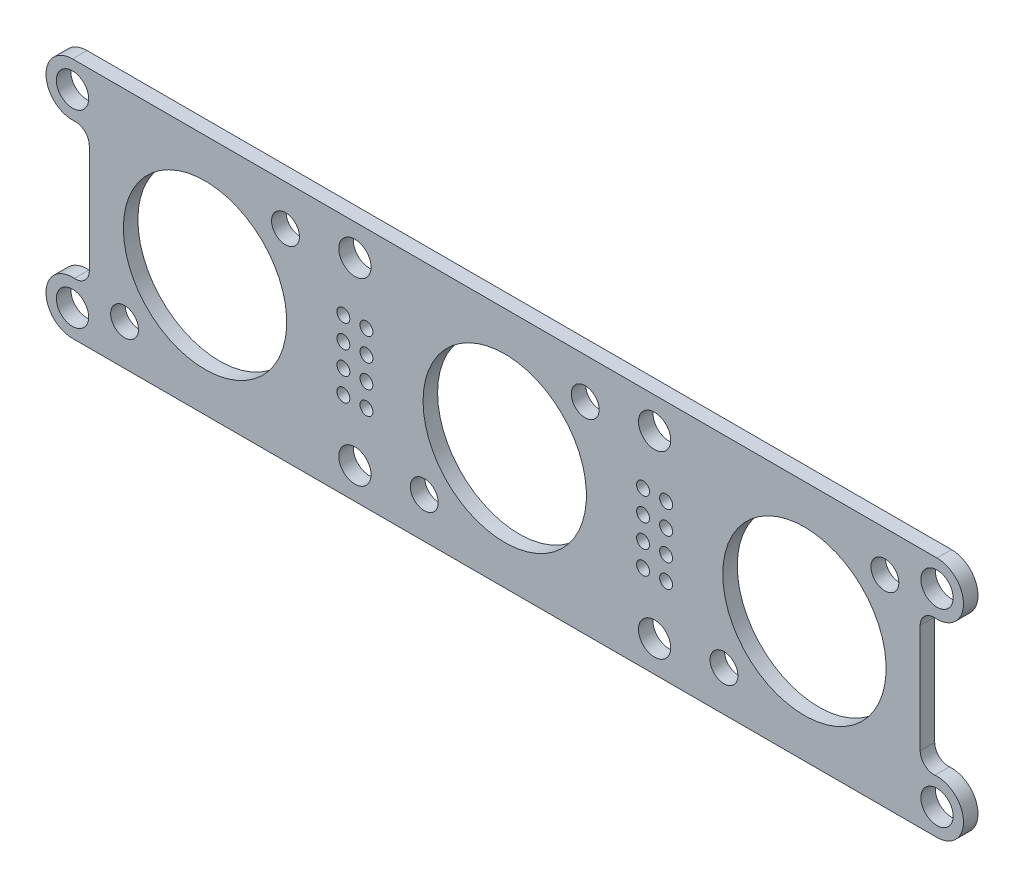
SolidWorks part; units mm, degrees
ref_plane "Front Plane" through (0, 0, 0) normal (0, 0, 1) x (1, 0, 0)
ref_plane "Top Plane" through (0, 0, 0) normal (0, 1, 0) x (1, 0, 0)
ref_plane "Right Plane" through (0, 0, 0) normal (1, 0, 0) x (0, 0, -1)
sketch "Sketch1" plane through (0, 0, -38.7925) normal (0, 0, -1) x (-1, 0, 0)
  line L72 (23.8125, 6.6675) -> (-23.8125, 6.6675)
  line L74 (-23.8125, -6.6675) -> (23.8125, -6.6675)
  line L75 (22.887, -2.9905) -> (22.887, 2.9905)
  line L76 (23.8125, 6.6675) -> (-23.8125, 6.6675)
  line L78 (-23.8125, -6.6675) -> (23.8125, -6.6675)
  line L152 (-22.887, 2.9905) -> (-22.887, -2.9905)
  line L153 (-22.887, 2.9905) -> (-22.887, -2.9905)
  line L164 (22.887, -2.9905) -> (22.887, 2.9905)
  circle A74 centre (16.51, 0) radius 4.5 construction
  circle A75 centre (0, 0) radius 4.5 construction
  circle A76 centre (-16.51, 0) radius 4.5 construction
  arc A78 (23.7051, 3.7505) -> (23.8125, 6.6675) centre (23.8125, 5.207) ccw
  arc A79 (-23.8125, 6.6675) -> (-23.7051, 3.7505) centre (-23.8125, 5.207) ccw
  arc A80 (-23.7051, -3.7505) -> (-23.8125, -6.6675) centre (-23.8125, -5.207) ccw
  arc A81 (23.8125, -6.6675) -> (23.7051, -3.7505) centre (23.8125, -5.207) ccw
  arc A82 (23.7051, 3.7505) -> (23.8125, 6.6675) centre (23.8125, 5.207) ccw
  arc A83 (-23.8125, 6.6675) -> (-23.7051, 3.7505) centre (-23.8125, 5.207) ccw
  arc A84 (-23.7051, -3.7505) -> (-23.8125, -6.6675) centre (-23.8125, -5.207) ccw
  arc A85 (23.8125, -6.6675) -> (23.7051, -3.7505) centre (23.8125, -5.207) ccw
  circle A88 centre (16.51, 0) radius 4.5
  circle A89 centre (0, 0) radius 4.5
  circle A90 centre (-16.51, 0) radius 4.5
  arc A173 (-22.887, 2.9905) -> (-23.7051, 3.7505) centre (-23.649, 2.9905) ccw
  arc A174 (-22.887, 2.9905) -> (-23.7051, 3.7505) centre (-23.649, 2.9905) ccw
  arc A175 (-23.7051, -3.7505) -> (-22.887, -2.9905) centre (-23.649, -2.9905) ccw
  arc A176 (-23.7051, -3.7505) -> (-22.887, -2.9905) centre (-23.649, -2.9905) ccw
  arc A195 (23.7051, 3.7505) -> (22.887, 2.9905) centre (23.649, 2.9905) ccw
  arc A196 (23.7051, 3.7505) -> (22.887, 2.9905) centre (23.649, 2.9905) ccw
  arc A197 (22.887, -2.9905) -> (23.7051, -3.7505) centre (23.649, -2.9905) ccw
  arc A198 (22.887, -2.9905) -> (23.7051, -3.7505) centre (23.649, -2.9905) ccw
  dimension "D1" = 0.127
extrude "Boss-Extrude1" add sketch "Sketch1" along normal blind 0.8
sketch "Sketch2" plane through (0, 0, -39.5925) normal (0, 0, -1) x (-1, 0, 0)
  circle A1 centre (-12.0779, -4.4321) radius 0.7679
  circle A2 centre (-12.0779, -4.4321) radius 0.7679
  circle A5 centre (-20.9421, 4.4321) radius 0.7679
  circle A6 centre (-20.9421, 4.4321) radius 0.7679
  circle A11 centre (-4.4321, 4.4321) radius 0.7679
  circle A12 centre (-4.4321, 4.4321) radius 0.7679
  circle A13 centre (-7.62, -1.905) radius 0.3556
  circle A17 centre (-7.62, -1.905) radius 0.3556
  circle A23 centre (-8.89, -1.905) radius 0.3556
  circle A27 centre (20.9421, -4.4321) radius 0.7679
  circle A28 centre (20.9421, -4.4321) radius 0.7679
  circle A31 centre (12.0779, 4.4321) radius 0.7679
  circle A32 centre (12.0779, 4.4321) radius 0.7679
  circle A35 centre (4.4321, -4.4321) radius 0.7679
  circle A36 centre (4.4321, -4.4321) radius 0.7679
  circle A37 centre (-8.89, -1.905) radius 0.3556
  circle A39 centre (-7.62, 1.905) radius 0.3556
  circle A41 centre (-7.62, 1.905) radius 0.3556
  circle A43 centre (-8.89, 1.905) radius 0.3556
  circle A45 centre (-8.89, 1.905) radius 0.3556
  circle A47 centre (-7.62, 0.635) radius 0.3556
  circle A49 centre (-7.62, 0.635) radius 0.3556
  circle A51 centre (-8.89, 0.635) radius 0.3556
  circle A53 centre (-8.89, 0.635) radius 0.3556
  circle A55 centre (-7.62, -0.635) radius 0.3556
  circle A145 centre (0, 0) radius 4.5 construction
  circle A146 centre (0, 0) radius 4.5
  circle A226 centre (-7.62, -0.635) radius 0.3556
  circle A227 centre (-8.89, -0.635) radius 0.3556
  circle A228 centre (-8.89, -0.635) radius 0.3556
  circle A247 centre (8.89, 1.905) radius 0.3556
  circle A248 centre (8.89, 1.905) radius 0.3556
  circle A249 centre (7.62, 1.905) radius 0.3556
  circle A250 centre (7.62, 1.905) radius 0.3556
  circle A263 centre (8.89, -1.905) radius 0.3556
  circle A264 centre (8.89, -1.905) radius 0.3556
  circle A265 centre (7.62, -1.905) radius 0.3556
  circle A266 centre (7.62, -1.905) radius 0.3556
  circle A267 centre (8.89, -0.635) radius 0.3556
  circle A268 centre (8.89, -0.635) radius 0.3556
  circle A269 centre (7.62, -0.635) radius 0.3556
  circle A270 centre (7.62, -0.635) radius 0.3556
  circle A271 centre (8.89, 0.635) radius 0.3556
  circle A272 centre (8.89, 0.635) radius 0.3556
  circle A273 centre (7.62, 0.635) radius 0.3556
  circle A274 centre (7.62, 0.635) radius 0.3556
  dimension "D1" = 0
  dimension "D3" = 0
  dimension "D5" = 0
  dimension "D6" = 0
  dimension "D9" = 0
  dimension "D10" = 0
  dimension "D11" = 0
  dimension "D12" = 0
  dimension "D14" = 0
  dimension "D16" = 0
  dimension "D18" = 0
  dimension "D19" = 0
  dimension "D20" = 0
  dimension "D21" = 0
  dimension "D31" = 0
  dimension "D32" = 0
  dimension "D39" = 0
  dimension "D40" = 0
  dimension "D41" = 0
  dimension "D42" = 0
  dimension "D43" = 0
  dimension "D44" = 0
extrude "Cut-Extrude1" cut sketch "Sketch2" against normal through all
sketch "Sketch3" plane through (0, 0, -39.5925) normal (0, 0, -1) x (-1, 0, 0)
  circle A0 centre (-23.8125, 5.207) radius 0.889
  circle A1 centre (-23.8125, -5.207) radius 0.889
  circle A2 centre (23.8125, 5.207) radius 0.889
  circle A3 centre (23.8125, -5.207) radius 0.889
  circle A4 centre (-8.255, 4.953) radius 0.889
  circle A5 centre (8.255, 4.953) radius 0.889
  circle A6 centre (8.255, -4.953) radius 0.889
  circle A7 centre (-8.255, -4.953) radius 0.889
  dimension "D1" = 1.778
  dimension "D2" = 47.625
  dimension "D3" = 10.414
extrude "Cut-Extrude2" cut sketch "Sketch3" against normal through all both and the other way through all
sketch "Sketch4" plane through (0, 0, -39.5925) normal (0, 0, -1) x (-1, 0, 0)
  line L0 (-23.8125, -6.6675) -> (-23.8125, -5.207) construction
  line L1 (-23.8125, -5.207) -> (-23.7051, -3.7505) construction
  line L2 (-23.7051, -3.7505) -> (-23.649, -2.9905) construction
  line L3 (-23.649, -2.9905) -> (-22.887, -2.9905) construction
  line L4 (-22.887, 2.9905) -> (-22.887, -2.9905)
  line L5 (-23.8125, -6.6675) -> (23.8125, -6.6675)
  line L6 (22.887, -2.9905) -> (22.887, 2.9905)
  line L7 (23.8125, 6.6675) -> (-23.8125, 6.6675)
  line L8 (-22.887, 2.9905) -> (-22.887, -2.9905)
  line L9 (-23.8125, -6.6675) -> (23.8125, -6.6675)
  line L10 (22.887, -2.9905) -> (22.887, 2.9905)
  line L11 (23.8125, 6.6675) -> (-23.8125, 6.6675)
  arc A8 (-22.887, 2.9905) -> (-23.7051, 3.7505) centre (-23.649, 2.9905) ccw
  arc A9 (-23.7051, -3.7505) -> (-22.887, -2.9905) centre (-23.649, -2.9905) ccw
  arc A10 (-23.7051, -3.7505) -> (-23.8125, -6.6675) centre (-23.8125, -5.207) ccw
  arc A11 (23.8125, -6.6675) -> (23.7051, -3.7505) centre (23.8125, -5.207) ccw
  arc A12 (22.887, -2.9905) -> (23.7051, -3.7505) centre (23.649, -2.9905) ccw
  arc A13 (23.7051, 3.7505) -> (22.887, 2.9905) centre (23.649, 2.9905) ccw
  arc A14 (23.7051, 3.7505) -> (23.8125, 6.6675) centre (23.8125, 5.207) ccw
  arc A15 (-23.8125, 6.6675) -> (-23.7051, 3.7505) centre (-23.8125, 5.207) ccw
  arc A16 (-22.887, 2.9905) -> (-23.7051, 3.7505) centre (-23.649, 2.9905) ccw
  arc A17 (-23.7051, -3.7505) -> (-22.887, -2.9905) centre (-23.649, -2.9905) ccw
  arc A18 (-23.7051, -3.7505) -> (-23.8125, -6.6675) centre (-23.8125, -5.207) ccw
  arc A19 (23.8125, -6.6675) -> (23.7051, -3.7505) centre (23.8125, -5.207) ccw
  arc A20 (22.887, -2.9905) -> (23.7051, -3.7505) centre (23.649, -2.9905) ccw
  arc A21 (23.7051, 3.7505) -> (22.887, 2.9905) centre (23.649, 2.9905) ccw
  arc A22 (23.7051, 3.7505) -> (23.8125, 6.6675) centre (23.8125, 5.207) ccw
  arc A23 (-23.8125, 6.6675) -> (-23.7051, 3.7505) centre (-23.8125, 5.207) ccw
  point P0 (-16.51, 0)
  point P8 (8.89, -1.905)
  point P13 (-25.272, -5.1532)
  point P16 (-7.62, -1.905)
  point P21 (25.272, -5.1532)
  point P24 (25.272, -6.6675)
  point P25 (25.272, -5.1532)
  point P27 (-8.255, -4.953)
  dimension "D4" = 50.544
  dimension "D2" = 184.219
  dimension "D3" = 94.219
  dimension "D1" = 0
ref_plane "Plane1" through (7.62, 0, 0) normal (1, 0, 0) x (0, 0, -1)
